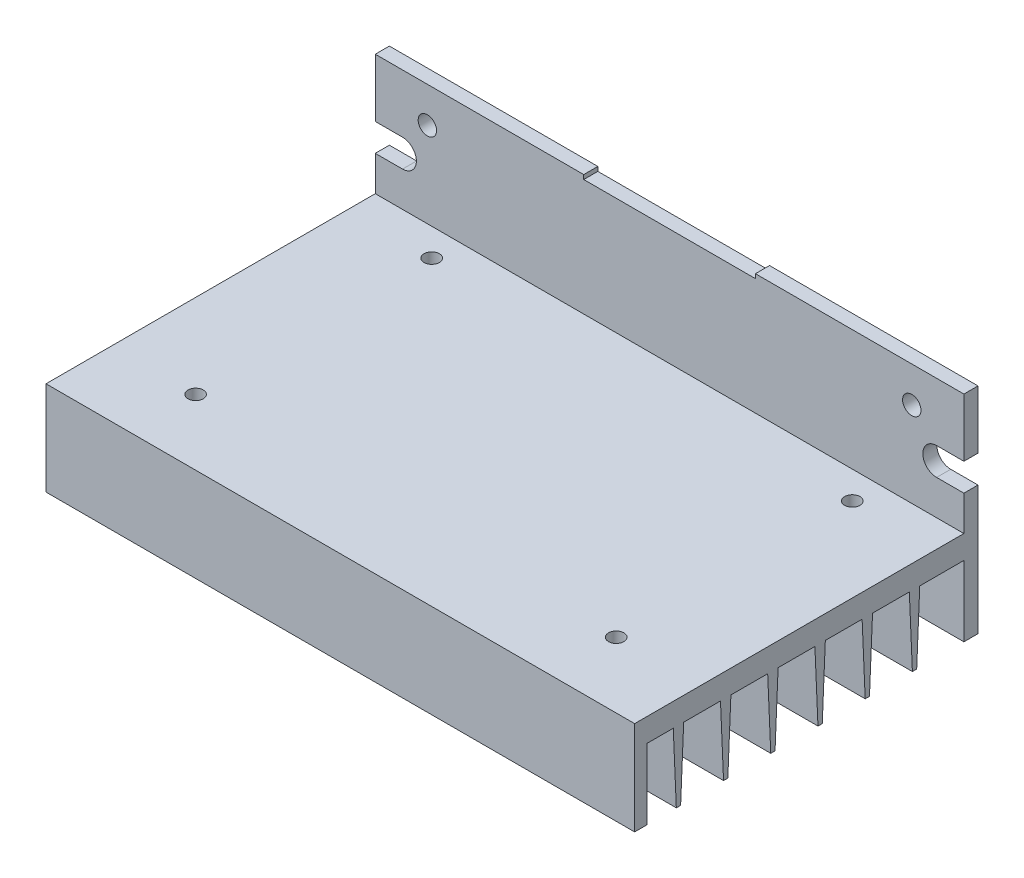
SolidWorks part; units mm, degrees
material "356.0-T6 Permanent Mold cast (SS)"
ref_plane "Front Plane" through (0, 0, 0) normal (0, 0, 1) x (1, 0, 0)
ref_plane "Top Plane" through (0, 0, 0) normal (0, 1, 0) x (1, 0, 0)
ref_plane "Right Plane" through (0, 0, 0) normal (1, 0, 0) x (0, 0, -1)
sketch "Sketch1" plane through (0, 0, 0) normal (0, 1, 0) x (1, 0, 0)
  line L1 (-48, 28) -> (48, 28)
  line L2 (-48, 28) -> (-48, -28)
  line L3 (-48, -28) -> (48, -28)
  line L4 (48, 28) -> (48, -28)
  line L5 (-48, 28) -> (48, -28) construction
  line L6 (-48, -28) -> (48, 28) construction
  point P0 (0, 0)
  dimension "D1" = 96
  dimension "D2" = 56
extrude "Boss-Extrude1" add sketch "Sketch1" along normal blind 3.8
sketch "Sketch2" plane through (0, 0, -28) normal (0, 0, -1) x (-1, 0, 0)
  line L0 (-48, 3.8) -> (-48, 0) construction
  line L1 (-48, 23.5) -> (48, 23.5)
  line L2 (-48, 23.5) -> (-48, -11.5)
  line L3 (-48, -11.5) -> (48, -11.5)
  line L4 (48, 23.5) -> (48, -11.5)
  line L5 (48, 3.8) -> (48, 0) construction
  line L7 (-48, 0) -> (48, 0) construction
  dimension "D1" = 35
  dimension "D2" = 11.5
extrude "Boss-Extrude2" add sketch "Sketch2" against normal blind 2.3
sketch "Sketch3" plane through (0, 0, -25.7) normal (0, 0, -1) x (-1, 0, 0)
  line L0 (-52.45, 11.75) -> (-43.55, 11.75) construction
  line L1 (-48, 23.5) -> (-48, -11.5) construction
  line L2 (-52.45, 14) -> (-43.55, 14)
  line L3 (-52.45, 9.5) -> (-43.55, 9.5)
  line L4 (-43.55, 11.75) -> (-41.3, 11.75) construction
  line L5 (-48, -11.5) -> (48, -11.5) construction
  line L6 (48, 23.5) -> (-48, 23.5) construction
  arc A0 (-52.45, 14) -> (-52.45, 9.5) centre (-52.45, 11.75) ccw
  arc A1 (-43.55, 9.5) -> (-43.55, 14) centre (-43.55, 11.75) ccw
  point P4 (-48, 11.75)
  dimension "D2" = 4.5
  dimension "D1" = 6.7
  dimension "D3" = 9.5
  dimension "D4" = 23.25
extrude "Cut-Extrude1" cut sketch "Sketch3" along normal through all
sketch "Sketch4" plane through (0, 0, -25.7) normal (0, 0, 1) x (1, 0, 0)
  line L1 (48, 9.5) -> (48, 3.8) construction
  line L2 (-48, 23.5) -> (48, 23.5) construction
  circle A0 centre (39.5, 17.7) radius 1.5
  dimension "D3" = 3
  dimension "D1" = 5.8
  dimension "D2" = 8.5
extrude "Cut-Extrude2" cut sketch "Sketch4" against normal through all
mirror "Mirror1" about plane through (0, 0, 0) normal (1, 0, 0) of "Cut-Extrude2", "Cut-Extrude1"
sketch "Sketch5" plane through (0, 0, 0) normal (0, 1, 0) x (1, 0, 0)
  line L0 (48, -28) -> (48, 25.7) construction
  line L1 (-48, -28) -> (48, -28)
  line L2 (-48, -28) -> (-48, -26)
  line L3 (-48, -26) -> (48, -26)
  line L4 (48, -28) -> (48, -26)
  dimension "D1" = 2
extrude "Boss-Extrude3" add sketch "Sketch5" against normal up to surface (11.5 mm away) up to face at (0, -11.5, -26.85)
sketch "Sketch7" plane through (0, 0, 0) normal (1, 0, 0) x (0, 0, -1)
  line L0 (-21.7, 0) -> (-21.2, -11.5)
  line L1 (-21.2, -11.5) -> (-20.5, -11.5)
  line L2 (-20.5, -11.5) -> (-20, 0)
  line L3 (-20, 0) -> (-21.7, 0)
  line L4 (-26, 0) -> (25.7, 0) construction
  line L5 (25.7, -11.5) -> (28, -11.5) construction
  line L7 (-20.85, 0) -> (-20.85, -11.5) construction
  line L8 (-26, -11.5) -> (-26, 0) construction
  dimension "D1" = 1.7
  dimension "D2" = 0.7
  dimension "D3" = 4.3
extrude "Boss-Extrude5" add sketch "Sketch7" along normal up to surface and the other way up to surface up to face at (48, 18.75, -26.85) other way up to face at (-48, 18.75, -26.85)
pattern_linear "LPattern1" count 6 spacing 7.7 along (0, 0, -1) of "Boss-Extrude5"
sketch "Sketch8" plane through (0, 23.5, 0) normal (0, 1, 0) x (1, 0, 0)
  line L0 (-48, 28) -> (48, 28) construction
  line L1 (-14, 28) -> (14, 28)
  line L2 (-14, 28) -> (-14, 25.7)
  line L3 (-14, 25.7) -> (14, 25.7)
  line L4 (14, 28) -> (14, 25.7)
  line L5 (-48, 25.7) -> (48, 25.7) construction
  point P8 (0, 28)
  dimension "D1" = 28
extrude "Cut-Extrude3" cut sketch "Sketch8" against normal blind 0.7
hole_wizard "M3x0.5 Tapped Hole1" positions "Sketch9" profile "Sketch10" tap size "M3x0.5" standard "ANSI Metric" end condition through all
sketch "Sketch9" plane through (0, 3.8, 0) normal (0, 1, 0) x (1, 0, 0)
  line L7 (34.3, -17.3) -> (-34.3, -17.3) construction
  line L9 (0, 0) -> (0, -17.3) construction
  line L11 (-48, -28) -> (48, -28) construction
  point P0 (-34.3, -17.3)
  point P3 (34.3, -17.3)
  dimension "D2" = 68.6
  dimension "D3" = 10.7
sketch "Sketch10" plane through (-34.3, 3.8, 17.3) normal (1, 0, 0) x (0, 0, 1)
  line L0 (0, 0) -> (0, 15.3)
  line L1 (0, 15.3) -> (1.25, 15.3)
  line L2 (1.25, 15.3) -> (1.25, 0)
  line L5 (1.25, 0) -> (0, 0)
  line L11 (0, -6.35) -> (0, 107.95) construction
  dimension "Thru Tap Drill Dia." = 2.5
  dimension "Thru Tap Drill Depth" = 15.3
cosmetic thread "Hole Thread2" parameters "D2"=3
cosmetic thread "Hole Thread3" parameters "D2"=3
pattern_linear "LPattern2" count 2 spacing 38.5 along (0, 0, -1) of "M3x0.5 Tapped Hole1"
